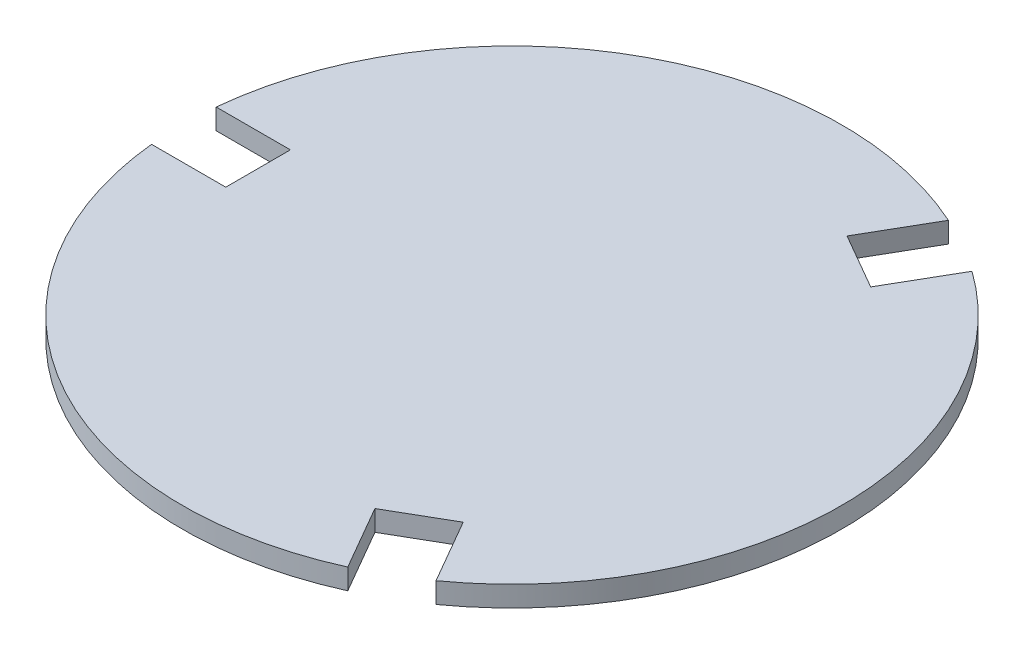
SolidWorks part; units mm, degrees
ref_plane "Front Plane" through (0, 0, 0) normal (0, 0, 1) x (1, 0, 0)
ref_plane "Top Plane" through (0, 0, 0) normal (0, 1, 0) x (1, 0, 0)
ref_plane "Right Plane" through (0, 0, 0) normal (1, 0, 0) x (0, 0, -1)
sketch "Sketch1" plane through (0, 0, 0) normal (0, 1, 0) x (1, 0, 0)
  circle A0 centre (0, 0) radius 50.8
  dimension "D1" = 101.6
extrude "Extrude1" add sketch "Sketch1" along normal blind 3.175
sketch "Sketch3" plane through (0, 3.175, 0) normal (0, 1, 0) x (-1, 0, 0)
  line L0 (50.8, 0) -> (0, 0) construction
  line L1 (42.1779, -4.9784) -> (39.1255, -4.9784)
  line L2 (50.5555, -4.9784) -> (42.1779, -4.9784)
  line L3 (39.1255, -4.9784) -> (39.1255, 4.9784)
  line L4 (50.5555, 4.9784) -> (42.3005, 4.9784)
  line L5 (50.5555, -4.9784) -> (50.5555, 4.9784) construction
  line L6 (39.1255, -8.1798) -> (39.1255, 10.511) construction
  line L7 (50.2686, -7.3284) -> (33.1572, -7.3284) construction
  line L8 (34.0455, -9.4786) -> (34.0455, -2.9283) construction
  line L9 (50.5555, -4.9784) -> (52.7503, -4.9784)
  line L10 (52.7503, -4.9784) -> (52.7503, 4.9784)
  line L11 (52.7503, 4.9784) -> (50.5555, 4.9784)
  line L12 (39.1255, 4.9784) -> (42.3005, 4.9784)
  line L13 (0, 0) -> (20.581, 35.6473) construction
  circle A0 centre (0, 0) radius 50.8 construction
  point P9 (35.2477, 0)
  dimension "D1" = 4.9784
  dimension "D2" = 11.43
  dimension "D3" = 2.35
  dimension "D4" = 5.08
  dimension "D5" = 11.43
  dimension "D6" = 60
  dimension "D7" = 41.162
extrude "Extrude2" cut sketch "Sketch3" against normal through all
sketch "Sketch5" plane through (0, 0, 0) normal (1, 0, 0) x (0, 0, -1)
  line L0 (0, 38.1783) -> (0, -21.3827) construction
pattern_circular "CirPattern1" count 2 over 120 about axis through (0, 38.1783, 0) along (0, -1, 0) of "Extrude2"
pattern_circular "CirPattern2" count 2 over 120 about axis through (0, 0, 0) along (0, 1, 0) of "Extrude2"
